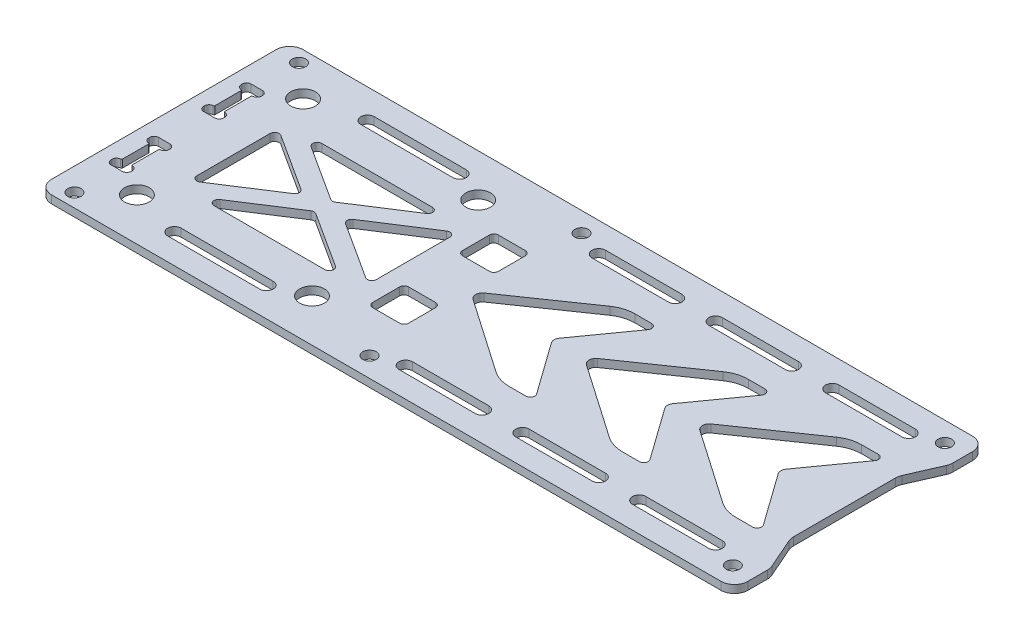
SolidWorks part; units mm, degrees
material "Thornel VCB-20 Carbon Cloth"
ref_plane "Front Plane" through (0, 0, 0) normal (0, 0, 1) x (1, 0, 0)
ref_plane "Top Plane" through (0, 0, 0) normal (0, 1, 0) x (1, 0, 0)
ref_plane "Right Plane" through (0, 0, 0) normal (1, 0, 0) x (0, 0, -1)
sketch "Sketch1" plane through (0, 0, 0) normal (0, 1, 0) x (1, 0, 0)
  line L0 (-173.6812, -17.3633) -> (49.4188, -17.3633) construction
  line L1 (-160.5312, -17.3633) -> (-160.5312, 10.6367)
  line L2 (-51.6812, -6.8633) -> (-51.6812, -27.8633)
  line L3 (-6.7652, -15.8713) -> (-22.4666, -6.2466)
  line L4 (-22.4666, -28.4799) -> (-6.7652, -18.8553)
  line L5 (-22.4666, -28.4799) -> (-6.7652, -18.8553) construction
  line L6 (-6.7652, -15.8713) -> (-22.4666, -6.2466) construction
  line L9 (-32.7705, -16.0785) -> (-41.743, -7.7805)
  line L10 (-41.743, -26.946) -> (-32.7705, -18.648)
  line L11 (-41.743, -26.946) -> (-32.7705, -18.648) construction
  line L12 (-32.7705, -16.0785) -> (-41.743, -7.7805) construction
  line L15 (-51.6812, -6.8633) -> (-51.6812, -27.8633) construction
  line L16 (49.4188, -40.3633) -> (49.4188, 5.6367)
  line L17 (43.7688, 10.6367) -> (15.9032, 10.6367)
  line L18 (15.266, 10.7788) -> (-9.569, 22.4322)
  line L19 (-11.1641, 22.2285) -> (-24.7146, 10.9825)
  line L20 (-25.6726, 10.6367) -> (-74.387, 10.6367)
  line L21 (-75.3488, 10.9857) -> (-88.7928, 22.2197)
  line L22 (-90.3999, 22.4228) -> (-114.8251, 10.7827)
  line L23 (-115.4704, 10.6367) -> (-168.6812, 10.6367)
  line L24 (-173.6812, 5.6367) -> (-173.6812, -40.3633)
  line L25 (-168.6812, -45.3633) -> (-115.4704, -45.3633)
  line L26 (-168.6812, -45.3633) -> (-115.4704, -45.3633) construction
  line L27 (-114.8251, -45.5092) -> (-90.3999, -57.1493)
  line L28 (-114.8251, -45.5092) -> (-90.3999, -57.1493) construction
  line L29 (-88.7928, -56.9462) -> (-75.3488, -45.7122)
  line L30 (-88.7928, -56.9462) -> (-75.3488, -45.7122) construction
  line L31 (-74.387, -45.3633) -> (-25.6726, -45.3633)
  line L32 (49.4188, -40.3633) -> (49.4188, 5.6367) construction
  line L33 (43.7688, 10.6367) -> (15.9032, 10.6367) construction
  line L34 (15.266, 10.7788) -> (-9.569, 22.4322) construction
  line L35 (-11.1641, 22.2285) -> (-24.7146, 10.9825) construction
  line L36 (-25.6726, 10.6367) -> (-74.387, 10.6367) construction
  line L37 (-75.3488, 10.9857) -> (-88.7928, 22.2197) construction
  line L38 (-90.3999, 22.4228) -> (-114.8251, 10.7827) construction
  line L39 (-115.4704, 10.6367) -> (-168.6812, 10.6367) construction
  line L40 (-173.6812, 5.6367) -> (-173.6812, -40.3633) construction
  line L50 (-167.6812, -18.8633) -> (-154.6812, -18.8633)
  line L51 (-56.6812, -25.6612) -> (-56.6812, -9.0653)
  line L52 (-56.6812, -25.6612) -> (-56.6812, -9.0653) construction
  line L53 (-59.6194, -7.7805) -> (-68.592, -16.0785)
  line L56 (-59.6194, -7.7805) -> (-68.592, -16.0785) construction
  line L57 (-98.4312, -26.9879) -> (-98.4312, -7.7386)
  line L58 (-92.2312, -3.8633) -> (-92.2312, -30.8633)
  line L59 (-77.7312, -2.3633) -> (-90.7312, -2.3633)
  line L60 (-92.2312, -3.8633) -> (-92.2312, -30.8633) construction
  line L61 (-76.2312, -30.8633) -> (-76.2312, -3.8633)
  line L63 (-77.7312, -2.3633) -> (-90.7312, -2.3633) construction
  line L66 (-98.4312, -26.9879) -> (-98.4312, -7.7386) construction
  line L67 (-101.0958, -6.2466) -> (-116.7972, -15.8713)
  line L70 (-101.0958, -6.2466) -> (-116.7972, -15.8713) construction
  line L71 (-126.7652, -15.8713) -> (-142.4666, -6.2466)
  line L72 (-142.4666, -28.4799) -> (-126.7652, -18.8553)
  line L73 (-142.4666, -28.4799) -> (-126.7652, -18.8553) construction
  line L74 (-126.7652, -15.8713) -> (-142.4666, -6.2466) construction
  line L77 (-136.3916, -5.5836) -> (-122.7302, -14.4008)
  line L78 (-108.1198, -2.3633) -> (-135.4426, -2.3633)
  line L79 (-120.8322, -14.4008) -> (-107.1709, -5.5836)
  line L80 (-136.3916, -5.5836) -> (-122.7302, -14.4008) construction
  line L81 (-108.1198, -2.3633) -> (-135.4426, -2.3633) construction
  line L82 (-120.8322, -14.4008) -> (-107.1709, -5.5836) construction
  line L83 (-154.6812, -15.8633) -> (-167.6812, -15.8633)
  line L85 (-154.6812, -15.8633) -> (-167.6812, -15.8633) construction
  line L86 (-118.0812, 5.6367) -> (-138.8812, 5.6367)
  line L87 (-138.8812, 2.6367) -> (-118.0812, 2.6367)
  line L88 (-118.0812, 5.6367) -> (-138.8812, 5.6367) construction
  line L89 (-138.8812, 2.6367) -> (-118.0812, 2.6367) construction
  line L90 (-62.0812, 2.6367) -> (-39.2812, 2.6367)
  line L91 (-39.2812, 5.6367) -> (-62.0812, 5.6367)
  line L92 (-156.5312, -4.2092) -> (-156.5312, -9.9173)
  line L93 (-157.6812, -2.7633) -> (-157.6812, -2.9633)
  line L94 (-154.1812, -1.7633) -> (-156.6812, -1.7633)
  line L95 (-153.1812, -2.9633) -> (-153.1812, -2.7633)
  line L96 (-154.3312, -9.9173) -> (-154.3312, -4.2092)
  line L97 (-153.1812, -11.3633) -> (-153.1812, -11.1633)
  line L98 (-156.6812, -12.3633) -> (-154.1812, -12.3633)
  line L99 (-157.6812, -11.1633) -> (-157.6812, -11.3633)
  line L100 (-156.5312, -4.2092) -> (-156.5312, -9.9173)
  line L101 (-157.6812, -2.7633) -> (-157.6812, -2.9633)
  line L102 (-154.1812, -1.7633) -> (-156.6812, -1.7633)
  line L103 (-153.1812, -2.9633) -> (-153.1812, -2.7633)
  line L104 (-154.3312, -9.9173) -> (-154.3312, -4.2092)
  line L105 (-153.1812, -11.3633) -> (-153.1812, -11.1633)
  line L106 (-156.6812, -12.3633) -> (-154.1812, -12.3633)
  line L107 (-157.6812, -11.1633) -> (-157.6812, -11.3633)
  line L108 (-62.0812, 2.6367) -> (-39.2812, 2.6367) construction
  line L109 (-39.2812, 5.6367) -> (-62.0812, 5.6367) construction
  line L110 (-160.5312, 10.6367) -> (-5.4812, 10.6367)
  line L111 (-5.4812, 10.6367) -> (-5.4812, -17.3633) construction
  line L112 (-39.2812, 2.6367) -> (-5.4812, 2.6367) construction
  line L113 (-8.9812, -17.3633) -> (-8.9812, -5.3633)
  line L114 (-8.9812, -5.3633) -> (-5.4812, 2.6367)
  line L115 (-5.4812, 2.6367) -> (-5.4812, 10.6367)
  line L116 (-8.9812, -17.3633) -> (-160.5312, -17.3633)
  line L523 (-49.6812, -27.8633) -> (-49.6812, -6.8633)
  line L524 (-25.1312, -7.7386) -> (-25.1312, -26.9879)
  line L541 (-25.1312, -7.7386) -> (-25.1312, -26.9879) construction
  line L542 (-44.6812, -9.0653) -> (-44.6812, -25.6612)
  line L543 (-44.6812, -9.0653) -> (-44.6812, -25.6612) construction
  line L544 (-49.6812, -27.8633) -> (-49.6812, -6.8633) construction
  line L545 (-167.6812, -18.8633) -> (-154.6812, -18.8633) construction
  line L546 (-68.592, -18.648) -> (-59.6194, -26.946)
  line L547 (-68.592, -18.648) -> (-59.6194, -26.946) construction
  line L548 (-116.7972, -18.8553) -> (-101.0958, -28.4799)
  line L549 (-76.2312, -30.8633) -> (-76.2312, -3.8633) construction
  line L550 (-90.7312, -32.3633) -> (-77.7312, -32.3633)
  line L551 (-90.7312, -32.3633) -> (-77.7312, -32.3633) construction
  line L552 (-116.7972, -18.8553) -> (-101.0958, -28.4799) construction
  line L553 (-74.387, -45.3633) -> (-25.6726, -45.3633) construction
  line L554 (-24.7146, -45.709) -> (-11.1641, -56.955)
  line L555 (-24.7146, -45.709) -> (-11.1641, -56.955) construction
  line L556 (-9.569, -57.1587) -> (15.266, -45.5053)
  line L557 (-9.569, -57.1587) -> (15.266, -45.5053) construction
  line L558 (15.9032, -45.3633) -> (43.7688, -45.3633)
  line L559 (15.9032, -45.3633) -> (43.7688, -45.3633) construction
  line L560 (-145.1312, -7.7386) -> (-145.1312, -26.9879)
  line L561 (-145.1312, -7.7386) -> (-145.1312, -26.9879) construction
  circle A1 centre (-155.4312, 7.6367) radius 1.5
  arc A2 (-167.6812, -15.8633) -> (-167.6812, -18.8633) centre (-167.6812, -17.3633) ccw
  arc A3 (-6.7652, -18.8553) -> (-6.7652, -15.8713) centre (-7.6798, -17.3633) ccw
  arc A4 (-6.7652, -18.8553) -> (-6.7652, -15.8713) centre (-7.6798, -17.3633) ccw construction
  arc A5 (-25.1312, -26.9879) -> (-22.4666, -28.4799) centre (-23.3812, -26.9879) ccw
  arc A9 (-32.7705, -18.648) -> (-32.7705, -16.0785) centre (-33.9587, -17.3633) ccw
  arc A10 (-32.7705, -18.648) -> (-32.7705, -16.0785) centre (-33.9587, -17.3633) ccw construction
  arc A11 (-44.6812, -25.6612) -> (-41.743, -26.946) centre (-42.9312, -25.6612) ccw
  arc A15 (-59.6194, -26.946) -> (-56.6812, -25.6612) centre (-58.4312, -25.6612) ccw
  arc A17 (49.4188, 5.6367) -> (43.7688, 10.6367) centre (43.7688, 4.9445) ccw
  arc A19 (-25.1312, -26.9879) -> (-22.4666, -28.4799) centre (-23.3812, -26.9879) ccw construction
  arc A20 (-44.6812, -25.6612) -> (-41.743, -26.946) centre (-42.9312, -25.6612) ccw construction
  arc A21 (-51.6812, -27.8633) -> (-50.6812, -28.8633) centre (-50.6812, -27.8633) ccw
  arc A22 (-51.6812, -27.8633) -> (-50.6812, -28.8633) centre (-50.6812, -27.8633) ccw construction
  arc A23 (-50.6812, -5.8633) -> (-51.6812, -6.8633) centre (-50.6812, -6.8633) ccw
  arc A24 (-168.6812, 10.6367) -> (-173.6812, 5.6367) centre (-168.6812, 5.6367) ccw
  arc A25 (-50.6812, -5.8633) -> (-51.6812, -6.8633) centre (-50.6812, -6.8633) ccw construction
  arc A26 (-59.6194, -26.946) -> (-56.6812, -25.6612) centre (-58.4312, -25.6612) ccw construction
  arc A27 (-68.592, -16.0785) -> (-68.592, -18.648) centre (-67.4038, -17.3633) ccw
  arc A28 (-68.592, -16.0785) -> (-68.592, -18.648) centre (-67.4038, -17.3633) ccw construction
  arc A29 (-92.2312, -30.8633) -> (-90.7312, -32.3633) centre (-90.7312, -30.8633) ccw
  arc A30 (-92.2312, -30.8633) -> (-90.7312, -32.3633) centre (-90.7312, -30.8633) ccw construction
  arc A31 (-90.7312, -2.3633) -> (-92.2312, -3.8633) centre (-90.7312, -3.8633) ccw
  arc A33 (49.4188, 5.6367) -> (43.7688, 10.6367) centre (43.7688, 4.9445) ccw construction
  arc A40 (-168.6812, 10.6367) -> (-173.6812, 5.6367) centre (-168.6812, 5.6367) ccw construction
  arc A48 (-90.7312, -2.3633) -> (-92.2312, -3.8633) centre (-90.7312, -3.8633) ccw construction
  arc A49 (-101.0958, -28.4799) -> (-98.4312, -26.9879) centre (-100.1812, -26.9879) ccw
  arc A50 (-101.0958, -28.4799) -> (-98.4312, -26.9879) centre (-100.1812, -26.9879) ccw construction
  arc A51 (-116.7972, -15.8713) -> (-116.7972, -18.8553) centre (-115.8826, -17.3633) ccw
  arc A56 (-116.7972, -15.8713) -> (-116.7972, -18.8553) centre (-115.8826, -17.3633) ccw construction
  arc A57 (-126.7652, -18.8553) -> (-126.7652, -15.8713) centre (-127.6798, -17.3633) ccw
  arc A61 (-126.7652, -18.8553) -> (-126.7652, -15.8713) centre (-127.6798, -17.3633) ccw construction
  arc A62 (-145.1312, -26.9879) -> (-142.4666, -28.4799) centre (-143.3812, -26.9879) ccw
  arc A63 (-145.1312, -26.9879) -> (-142.4666, -28.4799) centre (-143.3812, -26.9879) ccw construction
  arc A64 (-167.6812, -15.8633) -> (-167.6812, -18.8633) centre (-167.6812, -17.3633) ccw construction
  arc A65 (-154.6812, -18.8633) -> (-154.6812, -15.8633) centre (-154.6812, -17.3633) ccw
  arc A70 (-154.6812, -18.8633) -> (-154.6812, -15.8633) centre (-154.6812, -17.3633) ccw construction
  arc A75 (-22.4666, -6.2466) -> (-25.1312, -7.7386) centre (-23.3812, -7.7386) ccw
  arc A76 (-22.4666, -6.2466) -> (-25.1312, -7.7386) centre (-23.3812, -7.7386) ccw construction
  arc A77 (-41.743, -7.7805) -> (-44.6812, -9.0653) centre (-42.9312, -9.0653) ccw
  arc A81 (-41.743, -7.7805) -> (-44.6812, -9.0653) centre (-42.9312, -9.0653) ccw construction
  arc A82 (-56.6812, -9.0653) -> (-59.6194, -7.7805) centre (-58.4312, -9.0653) ccw
  arc A83 (-49.6812, -6.8633) -> (-50.6812, -5.8633) centre (-50.6812, -6.8633) ccw
  arc A87 (-49.6812, -6.8633) -> (-50.6812, -5.8633) centre (-50.6812, -6.8633) ccw construction
  circle A90 centre (-155.4312, 7.6367) radius 1.5
  circle A91 centre (-91.1312, 6.2367) radius 1.5
  circle A92 centre (-91.1312, 6.2367) radius 1.5
  circle A93 centre (-10.2312, 6.2367) radius 1.5
  arc A94 (-50.6812, -28.8633) -> (-49.6812, -27.8633) centre (-50.6812, -27.8633) ccw
  arc A95 (-50.6812, -28.8633) -> (-49.6812, -27.8633) centre (-50.6812, -27.8633) ccw construction
  arc A96 (-56.6812, -9.0653) -> (-59.6194, -7.7805) centre (-58.4312, -9.0653) ccw construction
  arc A97 (-98.4312, -7.7386) -> (-101.0958, -6.2466) centre (-100.1812, -7.7386) ccw
  arc A100 (-76.2312, -3.8633) -> (-77.7312, -2.3633) centre (-77.7312, -3.8633) ccw
  arc A101 (-76.2312, -3.8633) -> (-77.7312, -2.3633) centre (-77.7312, -3.8633) ccw construction
  arc A102 (43.7688, -45.3633) -> (49.4188, -40.3633) centre (43.7688, -39.671) ccw
  arc A103 (43.7688, -45.3633) -> (49.4188, -40.3633) centre (43.7688, -39.671) ccw construction
  arc A104 (15.266, 10.7788) -> (15.9032, 10.6367) centre (15.9032, 12.1367) ccw
  arc A105 (15.266, 10.7788) -> (15.9032, 10.6367) centre (15.9032, 12.1367) ccw construction
  arc A106 (-9.569, 22.4322) -> (-11.1641, 22.2285) centre (-10.2062, 21.0742) ccw
  arc A107 (-9.569, 22.4322) -> (-11.1641, 22.2285) centre (-10.2062, 21.0742) ccw construction
  arc A108 (-25.6726, 10.6367) -> (-24.7146, 10.9825) centre (-25.6726, 12.1367) ccw
  arc A109 (-25.6726, 10.6367) -> (-24.7146, 10.9825) centre (-25.6726, 12.1367) ccw construction
  arc A110 (-75.3488, 10.9857) -> (-74.387, 10.6367) centre (-74.387, 12.1367) ccw
  arc A111 (-75.3488, 10.9857) -> (-74.387, 10.6367) centre (-74.387, 12.1367) ccw construction
  circle A126 centre (-10.2312, 6.2367) radius 1.5
  arc A128 (-88.7928, 22.2197) -> (-90.3999, 22.4228) centre (-89.7546, 21.0687) ccw
  arc A129 (-88.7928, 22.2197) -> (-90.3999, 22.4228) centre (-89.7546, 21.0687) ccw construction
  arc A130 (-115.4704, 10.6367) -> (-114.8251, 10.7827) centre (-115.4704, 12.1367) ccw
  arc A131 (-115.4704, 10.6367) -> (-114.8251, 10.7827) centre (-115.4704, 12.1367) ccw construction
  arc A621 (-173.6812, -40.3633) -> (-168.6812, -45.3633) centre (-168.6812, -40.3633) ccw
  arc A622 (-173.6812, -40.3633) -> (-168.6812, -45.3633) centre (-168.6812, -40.3633) ccw construction
  arc A623 (-114.8251, -45.5092) -> (-115.4704, -45.3633) centre (-115.4704, -46.8633) ccw
  arc A624 (-114.8251, -45.5092) -> (-115.4704, -45.3633) centre (-115.4704, -46.8633) ccw construction
  arc A625 (-90.3999, -57.1493) -> (-88.7928, -56.9462) centre (-89.7546, -55.7952) ccw
  arc A626 (-90.3999, -57.1493) -> (-88.7928, -56.9462) centre (-89.7546, -55.7952) ccw construction
  arc A627 (-74.387, -45.3633) -> (-75.3488, -45.7122) centre (-74.387, -46.8633) ccw
  arc A628 (-74.387, -45.3633) -> (-75.3488, -45.7122) centre (-74.387, -46.8633) ccw construction
  arc A629 (-24.7146, -45.709) -> (-25.6726, -45.3633) centre (-25.6726, -46.8633) ccw
  arc A630 (-24.7146, -45.709) -> (-25.6726, -45.3633) centre (-25.6726, -46.8633) ccw construction
  arc A631 (-11.1641, -56.955) -> (-9.569, -57.1587) centre (-10.2062, -55.8007) ccw
  arc A632 (-11.1641, -56.955) -> (-9.569, -57.1587) centre (-10.2062, -55.8007) ccw construction
  arc A633 (15.9032, -45.3633) -> (15.266, -45.5053) centre (15.9032, -46.8633) ccw
  arc A634 (15.9032, -45.3633) -> (15.266, -45.5053) centre (15.9032, -46.8633) ccw construction
  arc A635 (-77.7312, -32.3633) -> (-76.2312, -30.8633) centre (-77.7312, -30.8633) ccw
  arc A636 (-77.7312, -32.3633) -> (-76.2312, -30.8633) centre (-77.7312, -30.8633) ccw construction
  arc A637 (-98.4312, -7.7386) -> (-101.0958, -6.2466) centre (-100.1812, -7.7386) ccw construction
  arc A638 (-142.4666, -6.2466) -> (-145.1312, -7.7386) centre (-143.3812, -7.7386) ccw
  arc A639 (-142.4666, -6.2466) -> (-145.1312, -7.7386) centre (-143.3812, -7.7386) ccw construction
  arc A640 (-135.4426, -2.3633) -> (-136.3916, -5.5836) centre (-135.4426, -4.1133) ccw
  arc A641 (-135.4426, -2.3633) -> (-136.3916, -5.5836) centre (-135.4426, -4.1133) ccw construction
  arc A642 (-107.1709, -5.5836) -> (-108.1198, -2.3633) centre (-108.1198, -4.1133) ccw
  arc A643 (-107.1709, -5.5836) -> (-108.1198, -2.3633) centre (-108.1198, -4.1133) ccw construction
  arc A644 (-122.7302, -14.4008) -> (-120.8322, -14.4008) centre (-121.7812, -12.9304) ccw
  arc A645 (-122.7302, -14.4008) -> (-120.8322, -14.4008) centre (-121.7812, -12.9304) ccw construction
  arc A647 (-140.3812, 4.1367) -> (-138.8812, 2.6367) centre (-138.8812, 4.1367) ccw
  arc A648 (-140.3812, 4.1367) -> (-138.8812, 2.6367) centre (-138.8812, 4.1367) ccw construction
  arc A649 (-138.8812, 5.6367) -> (-140.3812, 4.1367) centre (-138.8812, 4.1367) ccw
  arc A650 (-138.8812, 5.6367) -> (-140.3812, 4.1367) centre (-138.8812, 4.1367) ccw construction
  arc A651 (-116.5812, 4.1367) -> (-118.0812, 5.6367) centre (-118.0812, 4.1367) ccw
  arc A652 (-116.5812, 4.1367) -> (-118.0812, 5.6367) centre (-118.0812, 4.1367) ccw construction
  arc A653 (-118.0812, 2.6367) -> (-116.5812, 4.1367) centre (-118.0812, 4.1367) ccw
  arc A654 (-118.0812, 2.6367) -> (-116.5812, 4.1367) centre (-118.0812, 4.1367) ccw construction
  arc A655 (-156.5312, -4.2092) -> (-156.7612, -3.96) centre (-156.7812, -4.2092) ccw
  arc A656 (-156.5312, -4.2092) -> (-156.7612, -3.96) centre (-156.7812, -4.2092) ccw
  arc A657 (-157.6812, -2.9633) -> (-156.7612, -3.96) centre (-156.6812, -2.9633) ccw
  arc A658 (-157.6812, -2.9633) -> (-156.7612, -3.96) centre (-156.6812, -2.9633) ccw
  arc A659 (-156.6812, -1.7633) -> (-157.6812, -2.7633) centre (-156.6812, -2.7633) ccw
  arc A660 (-156.6812, -1.7633) -> (-157.6812, -2.7633) centre (-156.6812, -2.7633) ccw
  arc A661 (-153.1812, -2.7633) -> (-154.1812, -1.7633) centre (-154.1812, -2.7633) ccw
  arc A662 (-153.1812, -2.7633) -> (-154.1812, -1.7633) centre (-154.1812, -2.7633) ccw
  arc A663 (-154.1012, -3.96) -> (-153.1812, -2.9633) centre (-154.1812, -2.9633) ccw
  arc A664 (-154.1012, -3.96) -> (-153.1812, -2.9633) centre (-154.1812, -2.9633) ccw
  arc A665 (-154.1012, -3.96) -> (-154.3312, -4.2092) centre (-154.0812, -4.2092) ccw
  arc A666 (-154.1012, -3.96) -> (-154.3312, -4.2092) centre (-154.0812, -4.2092) ccw
  arc A667 (-154.3312, -9.9173) -> (-154.1012, -10.1665) centre (-154.0812, -9.9173) ccw
  arc A668 (-154.3312, -9.9173) -> (-154.1012, -10.1665) centre (-154.0812, -9.9173) ccw
  arc A669 (-153.1812, -11.1633) -> (-154.1012, -10.1665) centre (-154.1812, -11.1633) ccw
  arc A670 (-153.1812, -11.1633) -> (-154.1012, -10.1665) centre (-154.1812, -11.1633) ccw
  arc A671 (-154.1812, -12.3633) -> (-153.1812, -11.3633) centre (-154.1812, -11.3633) ccw
  arc A672 (-154.1812, -12.3633) -> (-153.1812, -11.3633) centre (-154.1812, -11.3633) ccw
  arc A673 (-157.6812, -11.3633) -> (-156.6812, -12.3633) centre (-156.6812, -11.3633) ccw
  arc A674 (-157.6812, -11.3633) -> (-156.6812, -12.3633) centre (-156.6812, -11.3633) ccw
  arc A675 (-156.7612, -10.1665) -> (-157.6812, -11.1633) centre (-156.6812, -11.1633) ccw
  arc A676 (-156.7612, -10.1665) -> (-157.6812, -11.1633) centre (-156.6812, -11.1633) ccw
  arc A677 (-156.7612, -10.1665) -> (-156.5312, -9.9173) centre (-156.7812, -9.9173) ccw
  arc A678 (-156.7612, -10.1665) -> (-156.5312, -9.9173) centre (-156.7812, -9.9173) ccw
  arc A679 (-63.5812, 4.1367) -> (-62.0812, 2.6367) centre (-62.0812, 4.1367) ccw
  arc A680 (-63.5812, 4.1367) -> (-62.0812, 2.6367) centre (-62.0812, 4.1367) ccw construction
  arc A681 (-62.0812, 5.6367) -> (-63.5812, 4.1367) centre (-62.0812, 4.1367) ccw
  arc A682 (-62.0812, 5.6367) -> (-63.5812, 4.1367) centre (-62.0812, 4.1367) ccw construction
  arc A683 (-37.7812, 4.1367) -> (-39.2812, 5.6367) centre (-39.2812, 4.1367) ccw
  arc A684 (-37.7812, 4.1367) -> (-39.2812, 5.6367) centre (-39.2812, 4.1367) ccw construction
  arc A685 (-39.2812, 2.6367) -> (-37.7812, 4.1367) centre (-39.2812, 4.1367) ccw
  arc A686 (-39.2812, 2.6367) -> (-37.7812, 4.1367) centre (-39.2812, 4.1367) ccw construction
  point P152 (0, 0)
  point P160 (0, 0)
  point P165 (-170.2317, -17.3633)
  point P166 (41.5939, -17.3633)
  dimension "D17" = 4
  dimension "D18" = 4.75
  dimension "D19" = 3.5
  dimension "D20" = 12
  dimension "D1" = 0
  dimension "D2" = 0
  dimension "D3" = 0
  dimension "D4" = 0
  dimension "D5" = 0
  dimension "D6" = 0
  dimension "D7" = 0
  dimension "D8" = 0
  dimension "D9" = 0
  dimension "D10" = 0
  dimension "D11" = 0
  dimension "D12" = 0
  dimension "D13" = 0
  dimension "D14" = 0
  dimension "D15" = 0
  dimension "D16" = 0
extrude "Boss-Extrude1" add sketch "Sketch1" along normal blind 1.75
sketch "Sketch2" plane through (0, 0, 0) normal (0, 1, 0) x (1, 0, 0)
  line L0 (-62.0812, 4.1367) -> (-39.2812, 4.1367) construction
  line L1 (-59.1812, 4.1367) -> (-42.1812, 4.1367) construction
  line L2 (-62.0812, 2.6367) -> (-39.2812, 2.6367)
  line L3 (-39.2812, 5.6367) -> (-62.0812, 5.6367)
  line L4 (-62.0812, 2.6367) -> (-39.2812, 2.6367) construction
  line L5 (-39.2812, 5.6367) -> (-62.0812, 5.6367) construction
  line L6 (-160.5312, -17.3633) -> (-8.9812, -17.3633)
  line L7 (-8.9812, -17.3633) -> (-8.9812, -5.3633)
  line L8 (-8.9812, -5.3633) -> (-5.4812, 2.6367)
  line L9 (-5.4812, 2.6367) -> (-5.4812, 10.6367)
  line L10 (-5.4812, 10.6367) -> (-160.5312, 10.6367)
  line L11 (-160.5312, 10.6367) -> (-160.5312, -17.3633)
  line L12 (-160.5312, -17.3633) -> (-8.9812, -17.3633) construction
  line L13 (-8.9812, -17.3633) -> (-8.9812, -5.3633) construction
  line L14 (-8.9812, -5.3633) -> (-5.4812, 2.6367) construction
  line L15 (-5.4812, 2.6367) -> (-5.4812, 10.6367) construction
  line L16 (-5.4812, 10.6367) -> (-160.5312, 10.6367) construction
  line L17 (-160.5312, 10.6367) -> (-160.5312, -17.3633) construction
  line L18 (-59.1812, 5.6367) -> (-42.1812, 5.6367)
  line L19 (-59.1812, 2.6367) -> (-42.1812, 2.6367)
  line L20 (-33.1812, 4.1367) -> (-16.1812, 4.1367) construction
  line L21 (-33.1812, 5.6367) -> (-16.1812, 5.6367)
  line L22 (-33.1812, 2.6367) -> (-16.1812, 2.6367)
  line L23 (-85.1812, 4.1367) -> (-68.1812, 4.1367) construction
  line L24 (-85.1812, 5.6367) -> (-68.1812, 5.6367)
  line L25 (-85.1812, 2.6367) -> (-68.1812, 2.6367)
  line L26 (-85.1812, 4.1367) -> (-160.5312, 4.1367) construction
  line L27 (-136.6812, 4.1367) -> (-116.1812, 4.1367) construction
  line L28 (-136.6812, 5.6367) -> (-116.1812, 5.6367)
  line L29 (-136.6812, 2.6367) -> (-116.1812, 2.6367)
  line L30 (-145.0312, -17.3633) -> (-145.0312, -7.3633)
  line L31 (-145.0312, -7.3633) -> (-129.5312, -17.3633)
  line L32 (-129.5312, -17.3633) -> (-145.0312, -17.3633)
  line L33 (-125.0312, -17.3633) -> (-125.0312, 10.6367) construction
  line L34 (-120.5312, -17.3633) -> (-105.0312, -17.3633)
  line L35 (-105.0312, -17.3633) -> (-105.0312, -7.3633)
  line L36 (-105.0312, -7.3633) -> (-120.5312, -17.3633)
  line L37 (-140.7529, -5.3633) -> (-109.3096, -5.3633)
  line L38 (-109.3096, -5.3633) -> (-125.0312, -15.5063)
  line L39 (-125.0312, -15.5063) -> (-140.7529, -5.3633)
  line L40 (-23.4812, -17.3633) -> (-13.4812, -3.3633)
  line L41 (-101.0312, -11.3633) -> (-93.0312, -11.3633)
  line L42 (-101.0312, -11.3633) -> (-101.0312, -3.3633)
  line L43 (-101.0312, -3.3633) -> (-93.0312, -3.3633)
  line L44 (-93.0312, -11.3633) -> (-93.0312, -3.3633)
  line L45 (-13.4812, -3.3633) -> (-21.4812, -3.3633)
  line L46 (-21.4812, -3.3633) -> (-41.7312, -17.3633)
  line L47 (-41.7312, -17.3633) -> (-23.4812, -17.3633)
  line L48 (-46.7312, -3.3633) -> (-66.9812, -17.3633)
  line L49 (-66.9812, -17.3633) -> (-48.7312, -17.3633)
  line L50 (-48.7312, -17.3633) -> (-38.7312, -3.3633)
  line L51 (-38.7312, -3.3633) -> (-46.7312, -3.3633)
  line L52 (-71.9812, -3.3633) -> (-92.2312, -17.3633)
  line L53 (-92.2312, -17.3633) -> (-73.9812, -17.3633)
  line L54 (-73.9812, -17.3633) -> (-63.9812, -3.3633)
  line L55 (-63.9812, -3.3633) -> (-71.9812, -3.3633)
  arc A0 (-59.1812, 5.6367) -> (-59.1812, 2.6367) centre (-59.1812, 4.1367) ccw
  arc A1 (-42.1812, 2.6367) -> (-42.1812, 5.6367) centre (-42.1812, 4.1367) ccw
  arc A2 (-33.1812, 5.6367) -> (-33.1812, 2.6367) centre (-33.1812, 4.1367) ccw
  arc A3 (-16.1812, 2.6367) -> (-16.1812, 5.6367) centre (-16.1812, 4.1367) ccw
  arc A12 (-85.1812, 5.6367) -> (-85.1812, 2.6367) centre (-85.1812, 4.1367) ccw
  arc A13 (-68.1812, 2.6367) -> (-68.1812, 5.6367) centre (-68.1812, 4.1367) ccw
  arc A14 (-136.6812, 5.6367) -> (-136.6812, 2.6367) centre (-136.6812, 4.1367) ccw
  arc A15 (-116.1812, 2.6367) -> (-116.1812, 5.6367) centre (-116.1812, 4.1367) ccw
  circle A16 centre (-148.0312, 1.1367) radius 2.75
  circle A17 centre (-109.0312, 1.1367) radius 2.75
  arc A52 (-63.5812, 4.1367) -> (-62.0812, 2.6367) centre (-62.0812, 4.1367) ccw
  arc A53 (-63.5812, 4.1367) -> (-62.0812, 2.6367) centre (-62.0812, 4.1367) ccw construction
  arc A54 (-62.0812, 5.6367) -> (-63.5812, 4.1367) centre (-62.0812, 4.1367) ccw
  arc A55 (-62.0812, 5.6367) -> (-63.5812, 4.1367) centre (-62.0812, 4.1367) ccw construction
  arc A56 (-37.7812, 4.1367) -> (-39.2812, 5.6367) centre (-39.2812, 4.1367) ccw
  arc A57 (-37.7812, 4.1367) -> (-39.2812, 5.6367) centre (-39.2812, 4.1367) ccw construction
  arc A58 (-39.2812, 2.6367) -> (-37.7812, 4.1367) centre (-39.2812, 4.1367) ccw
  arc A59 (-39.2812, 2.6367) -> (-37.7812, 4.1367) centre (-39.2812, 4.1367) ccw construction
  point P16 (-50.6812, 4.1367)
  point P24 (-50.6812, 4.1367)
  point P27 (-24.6812, 4.1367)
  point P34 (-76.6812, 4.1367)
  point P42 (-126.4312, 4.1367)
  point P62 (-125.0312, -5.3633)
  dimension "D12" = 5.5
  dimension "D3" = 3
  dimension "D4" = 17
  dimension "D6" = 9
  dimension "D8" = 9
  dimension "D9" = 3
  dimension "D10" = 20.5
  dimension "D11" = 31
  dimension "D13" = 9.5
  dimension "D14" = 12.5
  dimension "D16" = 39
  dimension "D17" = 15.5
  dimension "D18" = 15.5
  dimension "D19" = 10
  dimension "D20" = 4.5
  dimension "D21" = 16
  dimension "D22" = 4
  dimension "D23" = 14
  dimension "D24" = 4
  dimension "D25" = 8
  dimension "D26" = 4.5
  dimension "D27" = 8
  dimension "D28" = 14.5
  dimension "D29" = 18.25
  dimension "D31" = 7
  dimension "D32" = 10.7
  dimension "D33" = 6.5
  dimension "D1" = 0
  dimension "D2" = 0
  dimension "D5" = 2
  dimension "D7" = 2
  dimension "D15" = 2
  dimension "D30" = 3
extrude "Cut-Extrude2" cut sketch "Sketch2" along normal through all
fillet "Fillet1" radius 3 2 edges at (-5.4812, 0.875, -10.6367) (-160.5312, 0.875, -10.6367)
fillet "Fillet2" radius 3 2 edges at (-8.9812, 0.875, 5.3633) (-5.4812, 0.875, -2.6367)
fillet "Fillet3" radius 1 4 edges at (-93.0312, 0.875, 11.3633) (-101.0312, 0.875, 11.3633) (-101.0312, 0.875, 3.3633) (-93.0312, 0.875, 3.3633)
fillet "Fillet4" radius 1 5 edges at (-145.0312, 0.875, 7.3633) (-105.0312, 0.875, 7.3633) (-125.0312, 0.875, 15.5063) (-109.3096, 0.875, 5.3633) (-140.7529, 0.875, 5.3633)
fillet "Fillet5" radius 1 3 edges at (-63.9812, 0.875, 3.3633) (-38.7312, 0.875, 3.3633) (-13.4812, 0.875, 3.3633)
fillet "Fillet6" radius 7.5 3 edges at (-71.9812, 0.875, 3.3633) (-46.7312, 0.875, 3.3633) (-21.4812, 0.875, 3.3633)
mirror "Mirror1" about plane through (-8.9812, 1.75, 17.3633) normal (0, 0, -1) of bodies 102
fillet "Fillet7" radius 1 2 edges at (-120.5312, 0.875, 17.3633) (-129.5312, 0.875, 17.3633)
fillet "Fillet8" radius 1.5 3 edges at (-66.9812, 0.875, 17.3633) (-92.2312, 0.875, 17.3633) (-41.7312, 0.875, 17.3633)
fillet "Fillet9" radius 1.5 3 edges at (-73.9812, 0.875, 17.3633) (-48.7312, 0.875, 17.3633) (-23.4812, 0.875, 17.3633)
